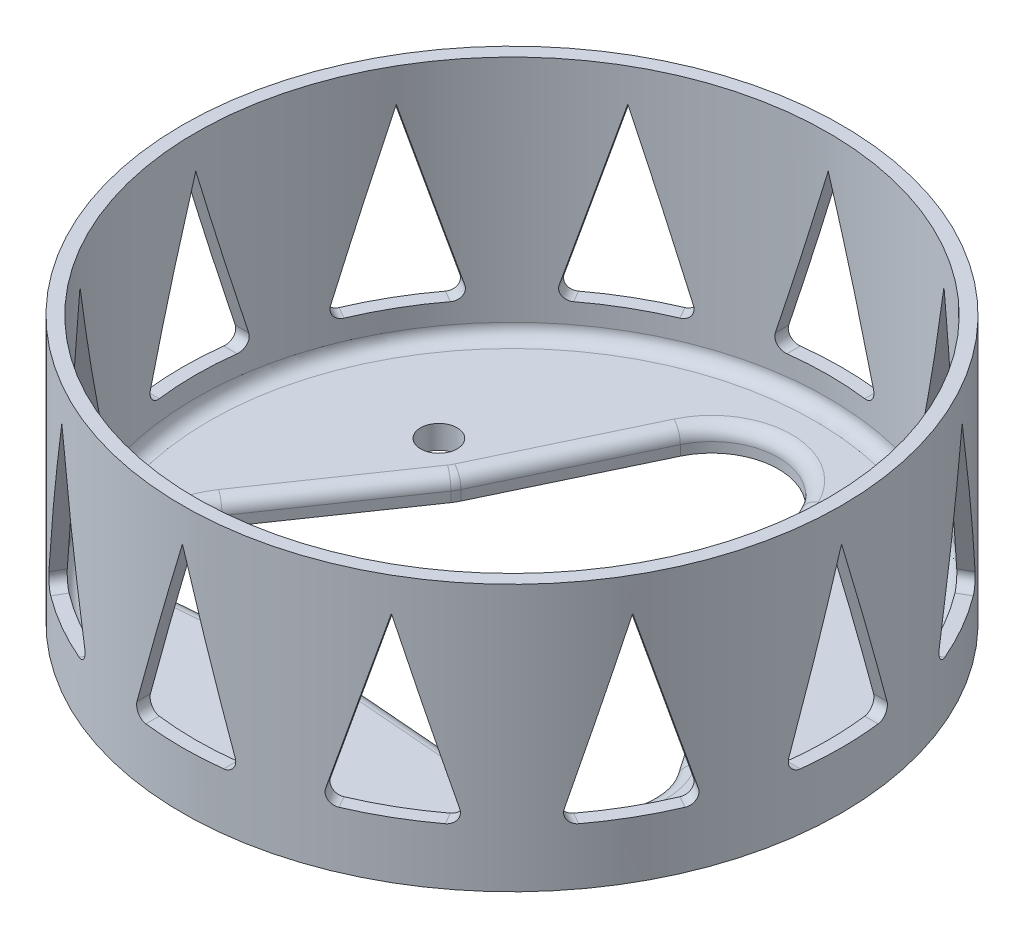
SolidWorks part; units mm, degrees
ref_plane "Спереди" through (0, 0, 0) normal (0, 0, 1) x (1, 0, 0)
ref_plane "Сверху" through (0, 0, 0) normal (0, 1, 0) x (1, 0, 0)
ref_plane "Справа" through (0, 0, 0) normal (1, 0, 0) x (0, 0, -1)
sketch "Эскиз2" plane through (0, 0, 0) normal (0, 0, 1) x (1, 0, 0)
  line L0 (0, -1536.0909) -> (0, 75268.4562) construction
  line L1 (0, 0) -> (49.5, 0)
  line L2 (49.5, 0) -> (49.5, 40)
  line L3 (49.5, 40) -> (47.5, 40)
  line L4 (47.5, 40) -> (47.5, 3.5)
  line L5 (47.5, 3.5) -> (0, 3.5)
  line L6 (0, 3.5) -> (0, 0)
  dimension "D1" = 40
  dimension "D2" = 2
  dimension "D3" = 99
  dimension "D4" = 3.5
revolve "Повернуть1" add sketch "Эскиз2" angle 360 about L0
sketch "Эскиз3" plane through (0, 0, 0) normal (0, 1, 0) x (1, 0, 0)
  line L0 (0, -1000) -> (0, 49000) construction
  circle A0 centre (0, 0) radius 30 construction
  circle A1 centre (0, -30) radius 2.75
  circle A2 centre (-25.9808, 15) radius 2.75
  circle A3 centre (25.9808, 15) radius 2.75
  point P11 (0, 0)
  point P12 (0, 0)
  point P13 (0, 0)
  point P14 (6.5869, 0)
  point P15 (0, 0)
  point P16 (26.6904, 15)
  point P17 (25.9808, 15)
  point P18 (-25.9808, 15)
  dimension "D1" = 60
  dimension "D2" = 5.5
  dimension "D3" = 120
  dimension "D4" = 120
extrude "Вырез-Вытянуть4" cut sketch "Эскиз3" along direction (0, 1, 0) on the side of the normal through all contours A2 | A1 | A3
sketch "Эскиз6" plane through (0, 0, 0) normal (0, -1, 0) x (1, 0, 0)
  line L0 (0, 0) -> (0, -50000) construction
  line L1 (-34.2202, 9.3333) -> (-20.2131, -11.0333)
  line L2 (-9.0272, -34.3023) -> (-19.6617, -11.9884)
  line L3 (25.193, 24.9689) -> (0.5514, 23.0218)
  line L4 (-25.193, 24.9689) -> (-0.5514, 23.0218)
  line L5 (9.0272, -34.3023) -> (19.6617, -11.9884)
  line L6 (34.2202, 9.3333) -> (20.2131, -11.0333)
  circle A0 centre (0, 0) radius 30
  circle A1 centre (0, -30) radius 10
  circle A2 centre (-25.9808, 15) radius 10
  circle A3 centre (25.9808, 15) radius 10
  circle A4 centre (0, 30) radius 7
  circle A5 centre (25.9808, -15) radius 7
  circle A6 centre (-25.9808, -15) radius 7
  point P14 (0, 0)
  point P20 (0, 0)
  point P26 (0, 0)
  point P33 (0, 0)
  dimension "D1" = 60
  dimension "D2" = 20
  dimension "D4" = 14
  dimension "D5" = 3
  dimension "D3" = 3
  dimension "D6" = 3
extrude "Вырез-Вытянуть5" cut sketch "Эскиз6" against normal through all contours A4 L0 A1 A0 L5 A5 L6 A3 L3 | L0 A4 L4 A0 A2 L1 A6 L2 A1 | A0 A2 | A0 A2 | L0 A0 A1 | A1 L0 A0 | L0 A1 A0 | A0 L0 A1 | A3 A0 | A0 A3 | A2 A0 L4 | A2 L1 A0 | A1 A0 L2 | A1 L5 A0 | A3 A0 L6 | A3 L3 A0
sketch "Эскиз7" plane through (0, 0, 0) normal (0, 0, 1) x (1, 0, 0)
  line L0 (0, -21.6497) -> (0, 49978.3503) construction
  line L1 (-8, 8.5) -> (8, 8.5)
  line L2 (8, 8.5) -> (0, 35)
  line L4 (47.5, 40) -> (-47.5, 40) construction
  line L5 (47.5, 3.5) -> (-47.5, 3.5) construction
  line L6 (-8, 8.5) -> (0, 35)
  point P10 (0, 8.5)
  point P12 (0, 8.5)
  dimension "D1" = 8
  dimension "D2" = 5
  dimension "D3" = 5
extrude "Вырез-Вытянуть6" cut sketch "Эскиз7" against normal through all
fillet "Скругление3" radius 1.6 2 edges at (-8, 8.5, -47.8354) (8, 8.5, -47.8354)
pattern_circular "Круговой массив1" count 12 over 360 about axis through (0, 0, 0) along (0, 1, 0) of "Вырез-Вытянуть6", "Скругление3"
fillet "Скругление1" radius 2 1 edges at (47.5, 3.5, 0)
fillet "Скругление2" radius 2 12 edges at (-19.9186, 3.5, -11.5) (-27.2167, 3.5, -0.85) (-34.641, 3.5, 20) (-12.8722, 3.5, 23.9953) (0, 3.5, 23) (12.8722, 3.5, 23.9953) (34.641, 3.5, 20) (27.2167, 3.5, -0.85) (19.9186, 3.5, -11.5) (14.3445, 3.5, -23.1453) (0, 3.5, -40) (-14.3445, 3.5, -23.1453)
